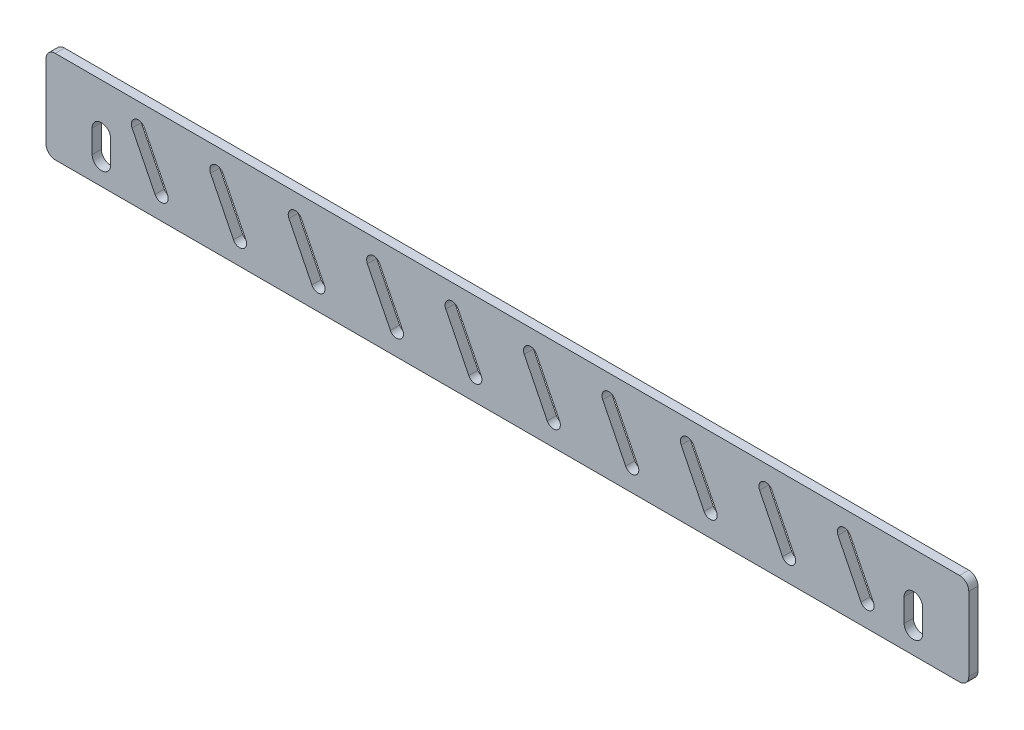
SolidWorks part; units mm, degrees
ref_plane "Front Plane" through (0, 0, 0) normal (0, 0, 1) x (1, 0, 0)
ref_plane "Top Plane" through (0, 0, 0) normal (0, 1, 0) x (1, 0, 0)
ref_plane "Right Plane" through (0, 0, 0) normal (1, 0, 0) x (0, 0, -1)
sketch "Sketch1" plane through (0, 0, 0) normal (0, 0, 1) x (1, 0, 0)
  line L1 (-100, 10) -> (100, 10)
  line L2 (-100, 10) -> (-100, -10)
  line L3 (-100, -10) -> (100, -10)
  line L4 (100, 10) -> (100, -10)
  line L5 (-100, 10) -> (100, -10) construction
  line L6 (-100, -10) -> (100, 10) construction
  point P0 (0, 0)
  dimension "D1" = 20
  dimension "D2" = 200
extrude "Boss-Extrude1" add sketch "Sketch1" along normal blind 2
fillet "Fillet1" radius 2 4 edges at (100, -10, 1) (100, 10, 1) (-100, -10, 1) (-100, 10, 1)
sketch "Sketch2" plane through (0, 0, 2) normal (0, 0, 1) x (1, 0, 0)
  line L0 (-87.995, 0) -> (-87.995, -5) construction
  line L1 (-85.99, 0) -> (-85.99, -5)
  line L2 (-90, 0) -> (-90, -5)
  line L3 (-100, 8) -> (-100, -8) construction
  line L6 (0, 28.6313) -> (0, -28.6313) construction
  line L7 (87.995, 0) -> (87.995, -5) construction
  line L8 (85.99, 0) -> (85.99, -5)
  line L9 (90, 0) -> (90, -5)
  line L10 (98, 10) -> (-98, 10) construction
  line L11 (-98, -10) -> (98, -10) construction
  arc A0 (-85.99, 0) -> (-90, 0) centre (-87.995, 0) ccw
  arc A1 (-90, -5) -> (-85.99, -5) centre (-87.995, -5) ccw
  arc A2 (85.99, 0) -> (90, 0) centre (87.995, 0) cw
  arc A3 (90, -5) -> (85.99, -5) centre (87.995, -5) cw
  point P2 (-87.995, -2.5)
  point P17 (0, 0)
  point P20 (87.995, -2.5)
  dimension "D3" = 10
  dimension "D4" = 5
  dimension "D1" = 4.01
  dimension "D2" = 10
extrude "Cut-Extrude1" cut sketch "Sketch2" against normal through all
sketch "Sketch3" plane through (0, 0, 2) normal (0, 0, 1) x (1, 0, 0)
  line L0 (-80, 5) -> (-75.0211, -5) construction
  line L1 (-78.6572, 5.6685) -> (-73.6784, -4.3315)
  line L2 (-81.3428, 4.3315) -> (-76.3639, -5.6685)
  line L3 (98, 10) -> (-98, 10) construction
  line L4 (-98, -10) -> (98, -10) construction
  line L5 (-100, 8) -> (-100, -8) construction
  line L6 (-63, 5) -> (-58.0211, -5) construction
  line L7 (-61.6572, 5.6685) -> (-56.6784, -4.3315)
  line L8 (-64.3428, 4.3315) -> (-59.3639, -5.6685)
  line L9 (-46, 5) -> (-41.0211, -5) construction
  line L10 (-44.6572, 5.6685) -> (-39.6784, -4.3315)
  line L11 (-47.3428, 4.3315) -> (-42.3639, -5.6685)
  line L12 (-29, 5) -> (-24.0211, -5) construction
  line L13 (-27.6572, 5.6685) -> (-22.6784, -4.3315)
  line L14 (-30.3428, 4.3315) -> (-25.3639, -5.6685)
  line L15 (-12, 5) -> (-7.0211, -5) construction
  line L16 (-10.6572, 5.6685) -> (-5.6784, -4.3315)
  line L17 (-13.3428, 4.3315) -> (-8.3639, -5.6685)
  line L18 (5, 5) -> (9.9789, -5) construction
  line L19 (6.3428, 5.6685) -> (11.3216, -4.3315)
  line L20 (3.6572, 4.3315) -> (8.6361, -5.6685)
  line L21 (22, 5) -> (26.9789, -5) construction
  line L22 (23.3428, 5.6685) -> (28.3216, -4.3315)
  line L23 (20.6572, 4.3315) -> (25.6361, -5.6685)
  line L24 (39, 5) -> (43.9789, -5) construction
  line L25 (40.3428, 5.6685) -> (45.3216, -4.3315)
  line L26 (37.6572, 4.3315) -> (42.6361, -5.6685)
  line L27 (56, 5) -> (60.9789, -5) construction
  line L28 (57.3428, 5.6685) -> (62.3216, -4.3315)
  line L29 (54.6572, 4.3315) -> (59.6361, -5.6685)
  line L30 (73, 5) -> (77.9789, -5) construction
  line L31 (74.3428, 5.6685) -> (79.3216, -4.3315)
  line L32 (71.6572, 4.3315) -> (76.6361, -5.6685)
  line L33 (100, -8) -> (100, 8) construction
  arc A0 (-78.6572, 5.6685) -> (-81.3428, 4.3315) centre (-80, 5) ccw
  arc A1 (-76.3639, -5.6685) -> (-73.6784, -4.3315) centre (-75.0211, -5) ccw
  arc A2 (-61.6572, 5.6685) -> (-64.3428, 4.3315) centre (-63, 5) ccw
  arc A3 (-59.3639, -5.6685) -> (-56.6784, -4.3315) centre (-58.0211, -5) ccw
  arc A4 (-44.6572, 5.6685) -> (-47.3428, 4.3315) centre (-46, 5) ccw
  arc A5 (-42.3639, -5.6685) -> (-39.6784, -4.3315) centre (-41.0211, -5) ccw
  arc A6 (-27.6572, 5.6685) -> (-30.3428, 4.3315) centre (-29, 5) ccw
  arc A7 (-25.3639, -5.6685) -> (-22.6784, -4.3315) centre (-24.0211, -5) ccw
  arc A8 (-10.6572, 5.6685) -> (-13.3428, 4.3315) centre (-12, 5) ccw
  arc A9 (-8.3639, -5.6685) -> (-5.6784, -4.3315) centre (-7.0211, -5) ccw
  arc A10 (6.3428, 5.6685) -> (3.6572, 4.3315) centre (5, 5) ccw
  arc A11 (8.6361, -5.6685) -> (11.3216, -4.3315) centre (9.9789, -5) ccw
  arc A12 (23.3428, 5.6685) -> (20.6572, 4.3315) centre (22, 5) ccw
  arc A13 (25.6361, -5.6685) -> (28.3216, -4.3315) centre (26.9789, -5) ccw
  arc A14 (40.3428, 5.6685) -> (37.6572, 4.3315) centre (39, 5) ccw
  arc A15 (42.6361, -5.6685) -> (45.3216, -4.3315) centre (43.9789, -5) ccw
  arc A16 (57.3428, 5.6685) -> (54.6572, 4.3315) centre (56, 5) ccw
  arc A17 (59.6361, -5.6685) -> (62.3216, -4.3315) centre (60.9789, -5) ccw
  arc A18 (74.3428, 5.6685) -> (71.6572, 4.3315) centre (73, 5) ccw
  arc A19 (76.6361, -5.6685) -> (79.3216, -4.3315) centre (77.9789, -5) ccw
  point P2 (-77.5106, 0)
  point P17 (-60.5106, 0)
  point P24 (-43.5106, 0)
  point P31 (-26.5106, 0)
  point P38 (-9.5106, 0)
  point P45 (7.4894, 0)
  point P52 (24.4894, 0)
  point P59 (41.4894, 0)
  point P66 (58.4894, 0)
  point P73 (75.4894, 0)
  dimension "D4" = 1.5
  dimension "D1" = 5
  dimension "D2" = 5
  dimension "D3" = 20
  dimension "D5" = 63.532
  dimension "D7" = 22.0211
  dimension "D6" = 10
extrude "Cut-Extrude2" cut sketch "Sketch3" against normal blind 10
